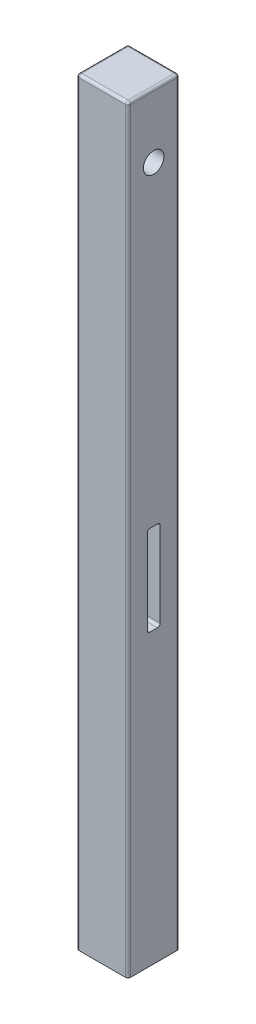
SolidWorks part; units mm, degrees
material "Ti-6Al-4VSolution treated and aged (SS)"
ref_plane "Front Plane" through (0, 0, 0) normal (0, 0, 1) x (1, 0, 0)
ref_plane "Top Plane" through (0, 0, 0) normal (0, 1, 0) x (1, 0, 0)
ref_plane "Right Plane" through (0, 0, 0) normal (1, 0, 0) x (0, 0, -1)
sketch "Sketch1" plane through (0, 0, 0) normal (0, 0, 1) x (1, 0, 0)
  line L1 (-10, 295.2) -> (10, 295.2)
  line L2 (-10, 295.2) -> (-10, 0)
  line L3 (-10, 0) -> (10, 0)
  line L4 (10, 295.2) -> (10, 0)
extrude "Boss-Extrude1" add sketch "Sketch1" along normal blind 20
sketch "Sketch2" plane through (10, 0, 0) normal (1, 0, 0) x (0, 0, -1)
  line L0 (0, 0) -> (0, 295.2) construction
  line L2 (-20, 295.2) -> (0, 295.2) construction
  circle A0 centre (-10, 270.2) radius 4
extrude "Cut-Extrude1" cut sketch "Sketch2" against normal up to next
sketch "Sketch3" plane through (0, 0, 0) normal (0, -1, 0) x (1, 0, 0)
  line L5 (-4, 7.5) -> (4, 7.5)
  line L7 (-5, 8.5) -> (-5, 11.5)
  line L18 (-4, 12.5) -> (4, 12.5)
  line L20 (5, 8.5) -> (5, 11.5)
  line L25 (-5, 7.5) -> (5, 12.5) construction
  line L26 (-5, 12.5) -> (5, 7.5) construction
  line L27 (-5.25, 2.5) -> (5.25, 2.5)
  line L28 (-6.25, 3.5) -> (-6.25, 16.5)
  line L29 (-5.25, 17.5) -> (5.25, 17.5)
  line L30 (6.25, 3.5) -> (6.25, 16.5)
  line L31 (-6.25, 2.5) -> (6.25, 17.5) construction
  line L32 (-6.25, 17.5) -> (6.25, 2.5) construction
  arc A0 (4, 7.5) -> (5, 8.5) centre (4, 8.5) ccw
  arc A1 (-4, 7.5) -> (-5, 8.5) centre (-4, 8.5) cw
  arc A2 (-5, 11.5) -> (-4, 12.5) centre (-4, 11.5) cw
  arc A3 (4, 12.5) -> (5, 11.5) centre (4, 11.5) cw
  arc A4 (5.25, 17.5) -> (6.25, 16.5) centre (5.25, 16.5) cw
  arc A5 (5.25, 2.5) -> (6.25, 3.5) centre (5.25, 3.5) ccw
  arc A6 (-5.25, 2.5) -> (-6.25, 3.5) centre (-5.25, 3.5) cw
  arc A7 (-6.25, 16.5) -> (-5.25, 17.5) centre (-5.25, 16.5) cw
  point P0 (0, 10)
  point P5 (0, 10)
  dimension "D6" = 1
  dimension "D1" = 10
  dimension "D2" = 5
  dimension "D3" = 10
  dimension "D4" = 12.5
  dimension "D5" = 15
extrude "Cut-Extrude2" cut sketch "Sketch3" against normal blind 14.1
sketch "Sketch5" plane through (-10, 0, 0) normal (-1, 0, 0) x (0, 0, 1)
  line L0 (20, 295.2) -> (0, 295.2) construction
  line L1 (8.5, 147.6) -> (11.5, 147.6)
  line L2 (7.5, 146.6) -> (7.5, 113.6)
  line L3 (8.5, 112.6) -> (11.5, 112.6)
  line L4 (12.5, 146.6) -> (12.5, 113.6)
  line L5 (20, 295.2) -> (20, 0) construction
  arc A0 (7.5, 113.6) -> (8.5, 112.6) centre (8.5, 113.6) ccw
  arc A1 (11.5, 112.6) -> (12.5, 113.6) centre (11.5, 113.6) ccw
  arc A2 (11.5, 147.6) -> (12.5, 146.6) centre (11.5, 146.6) cw
  arc A3 (8.5, 147.6) -> (7.5, 146.6) centre (8.5, 146.6) ccw
  point P6 (10, 147.6)
  point P13 (12.5, 112.6)
  point P16 (12.5, 147.6)
  point P19 (7.5, 147.6)
  dimension "D5" = 1
  dimension "D1" = 147.6
  dimension "D2" = 35
extrude "Cut-Extrude3" cut sketch "Sketch5" against normal through all
hole_wizard "M3x0.5 Tapped Hole1" positions "Sketch6" profile "Sketch7" tap size "M3x0.5" standard "ANSI Metric"
sketch "Sketch6" plane through (-10, 0, 0) normal (-1, 0, 0) x (0, 0, 1)
  line L0 (20, 295.2) -> (20, 0) construction
  line L1 (20, 0) -> (0, 0) construction
  line L2 (0, 295.2) -> (0, 0) construction
  point P0 (15, 7.05)
  point P7 (5, 7.05)
  dimension "D3" = 5
  dimension "D1" = 5
  dimension "D2" = 7.05
sketch "Sketch7" plane through (-10, 7.05, 15) normal (0, 1, 0) x (0, 0, 1)
  line L0 (0, 0) -> (0, 18.7511)
  line L1 (0, 18.7511) -> (1.25, 18)
  line L2 (1.25, 18) -> (1.25, 1.55)
  line L3 (1.25, 1.55) -> (2.8, 0)
  line L5 (2.8, 0) -> (0, 0)
  line L6 (-1.25, 1.55) -> (-2.8, 0) construction
  line L10 (0, 18.7511) -> (-1.25, 18) construction
  line L11 (0, -6.35) -> (0, 107.95) construction
  dimension "Tap Drill Dia." = 2.5
  dimension "Tap Drill Depth" = 18
  dimension "Near C'Sink Dia." = 5.6
  dimension "Near C'Sink Angle" = 90
  dimension "Drill Angle" = 118
cosmetic thread "Hole Thread2" parameters "D1"=18, "D2"=3
cosmetic thread "Hole Thread3" parameters "D1"=18, "D2"=3
fillet "Fillet1" radius 1 2 edges at (10, 295.2, 10) (-10, 295.2, 10)
fillet "Fillet2" radius 1 10 edges at (-10, 147.1, 0) (-9.7071, 294.9071, 0) (0, 295.2, 0) (9.7071, 294.9071, 0) (10, 147.1, 20) (9.7071, 294.9071, 20) (0, 295.2, 20) (-9.7071, 294.9071, 20) (10, 147.1, 0) (-10, 147.1, 20)
equation "\"D1@Boss-Extrude1\" = \"t_thigh\""
equation "\"L_upperThigh\"= 0.2952m"
equation "\"D2@Sketch1\"=\"L_upperThigh\""
equation "\"D2@Sketch2\" = \"t_thigh\" / 2"
equation "\"D4@Sketch5\" = \"t_thigh\" / 2"
equation "\"D3@Sketch3\" = \"t_thigh\" / 2"
equation "\"D5@Sketch3\" = \"t_thigh\" - 0.005m"
equation "\"D1@Sketch6\" = \"t_thigh\" / 4"
equation "\"t_thigh\"= 0.0200m"
equation "\"D1@Sketch5\"=\"L_upperThigh\"/2"
equation "\"D3@Sketch6\" = \"t_thigh\" / 4"
